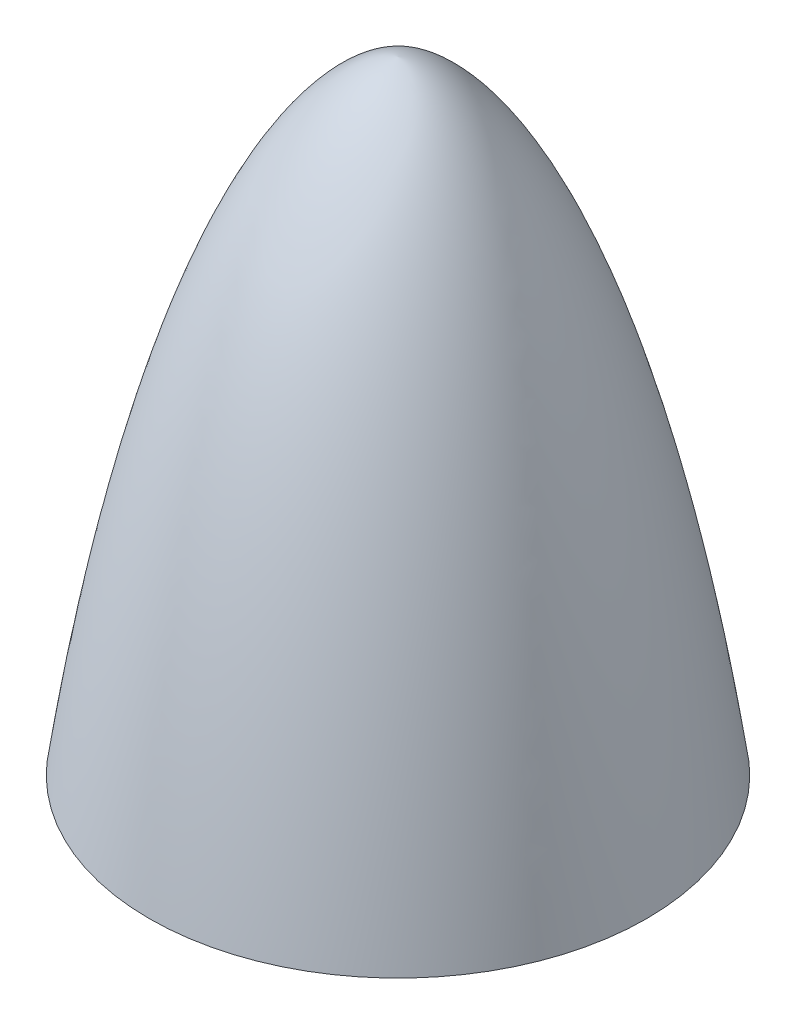
SolidWorks part; units mm, degrees
ref_plane "Front Plane" through (0, 0, 0) normal (0, 0, 1) x (1, 0, 0)
ref_plane "Top Plane" through (0, 0, 0) normal (0, 1, 0) x (1, 0, 0)
ref_plane "Right Plane" through (0, 0, 0) normal (1, 0, 0) x (0, 0, -1)
sketch "Sketch1" plane through (0, 0, 0) normal (0, 0, 1) x (1, 0, 0)
  line L0 (0, 0) -> (0, 635) construction
  line L1 (0, 0) -> (254, 0) construction
  line L2 (0, 635) -> (69.1657, 624.4601) construction
  line L3 (69.1657, 624.4601) -> (184.9533, 483.3833) construction
  line L4 (184.9533, 483.3833) -> (254, 0) construction
  line L5 (0, 635) -> (0, 0)
  line L6 (0, 0) -> (254, 0)
  spline S0 degree 3 poles (0, 635) (69.1657, 624.4601) (184.9533, 483.3833) (254, 0) knots 0 0 0 0 1 1 1 1
  point P6 (184.9533, 483.3833)
  point P7 (0, 0)
revolve "Revolve4" add sketch "Sketch1" angle 360 about L5
